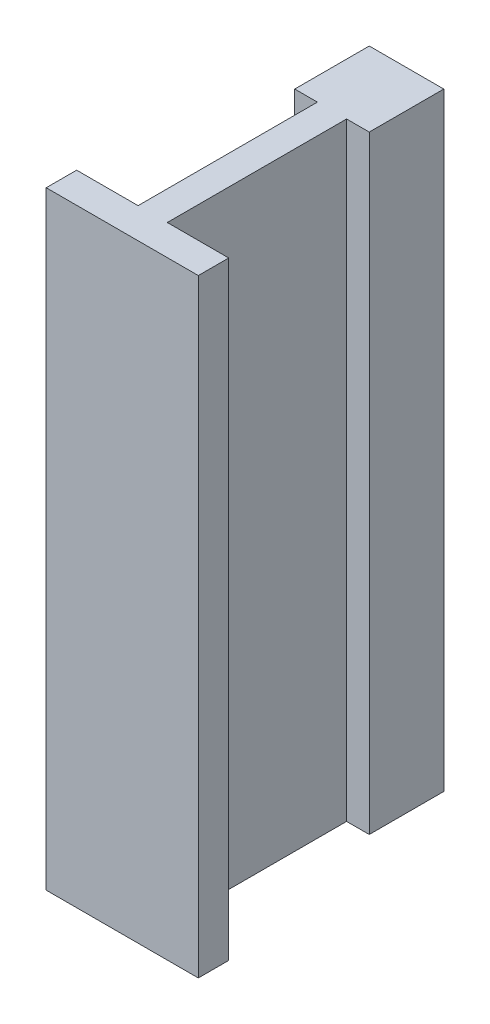
SolidWorks part; units mm, degrees
ref_plane "前基準面" through (0, 0, 0) normal (0, 0, 1) x (1, 0, 0)
ref_plane "上基準面" through (0, 0, 0) normal (0, 1, 0) x (1, 0, 0)
ref_plane "右基準面" through (0, 0, 0) normal (1, 0, 0) x (0, 0, -1)
sketch "草圖2" plane through (0, 0, 0) normal (0, 1, 0) x (1, 0, 0)
  line L0 (-1.1691, -3.0136) -> (-1.1691, -1.5591)
  line L1 (-1.1691, -1.5591) -> (-2.6591, -1.5591)
  line L2 (-2.6591, -1.5591) -> (-2.6591, 3.3409)
  line L3 (-2.6591, 3.3409) -> (2.2409, 3.3409)
  line L4 (2.2409, 3.3409) -> (2.2409, -1.5591)
  line L5 (2.2409, -1.5591) -> (0.7509, -1.5591)
  line L6 (0.7509, -1.5591) -> (0.7509, -3.0136)
  line L7 (0.7509, -3.0136) -> (-1.1691, -3.0136)
  dimension "D1" = 4.9
  dimension "D2" = 1.49
  dimension "D3" = 1.49
  dimension "D4" = 4.9
  dimension "D5" = 1.92
extrude "填料-伸長1" add sketch "草圖2" along normal blind 40
sketch "草圖3" plane through (0, 40, 0) normal (0, 1, 0) x (1, 0, 0)
  line L0 (-1.1691, -1.5591) -> (-1.1691, -4.3491) construction
  line L2 (-1.1691, -3.0136) -> (0.7509, -3.0136)
  line L3 (-1.1691, -3.0136) -> (-1.1691, -4.3491)
  line L4 (-1.1691, -4.3491) -> (0.7509, -4.3491)
  line L5 (0.7509, -3.0136) -> (0.7509, -4.3491)
  dimension "D1" = 2.79
extrude "填料-伸長2" add sketch "草圖3" against normal blind 40
sketch "草圖4" plane through (0, 0, 4.3491) normal (0, 0, 1) x (1, 0, 0)
  line L1 (-1.1691, 40) -> (0.7509, 40)
  line L2 (-1.1691, 40) -> (-1.1691, 0)
  line L3 (-1.1691, 0) -> (0.7509, 0)
  line L4 (0.7509, 40) -> (0.7509, 0)
extrude "填料-伸長3" add sketch "草圖4" along normal blind 1
sketch "草圖5" plane through (0, 0, 5.3491) normal (0, 0, 1) x (1, 0, 0)
  line L1 (-1.1691, 40) -> (0.7509, 40)
  line L2 (-1.1691, 40) -> (-1.1691, 0)
  line L3 (-1.1691, 0) -> (0.7509, 0)
  line L4 (0.7509, 40) -> (0.7509, 0)
extrude "填料-伸長4" add sketch "草圖5" along normal blind 10
sketch "草圖7" plane through (0, 40, 0) normal (0, 1, 0) x (1, 0, 0)
  line L0 (-0.2091, -1015.3491) -> (-0.2091, 48984.6509) construction
  line L1 (0.7509, -15.3491) -> (-1.1691, -15.3491) construction
  line L3 (-5.2091, -13.3491) -> (4.7909, -13.3491)
  line L4 (-5.2091, -13.3491) -> (-5.2091, -15.3491)
  line L5 (-5.2091, -15.3491) -> (4.7909, -15.3491)
  line L6 (4.7909, -13.3491) -> (4.7909, -15.3491)
  line L7 (-5.2091, -13.3491) -> (4.7909, -15.3491) construction
  line L8 (-5.2091, -15.3491) -> (4.7909, -13.3491) construction
  point P1 (-0.2091, -14.3491)
  point P5 (-0.2091, -15.3491)
  dimension "D1" = 10
  dimension "D2" = 2
  dimension "D3" = 0
extrude "填料-伸長5" add sketch "草圖7" against normal blind 40
